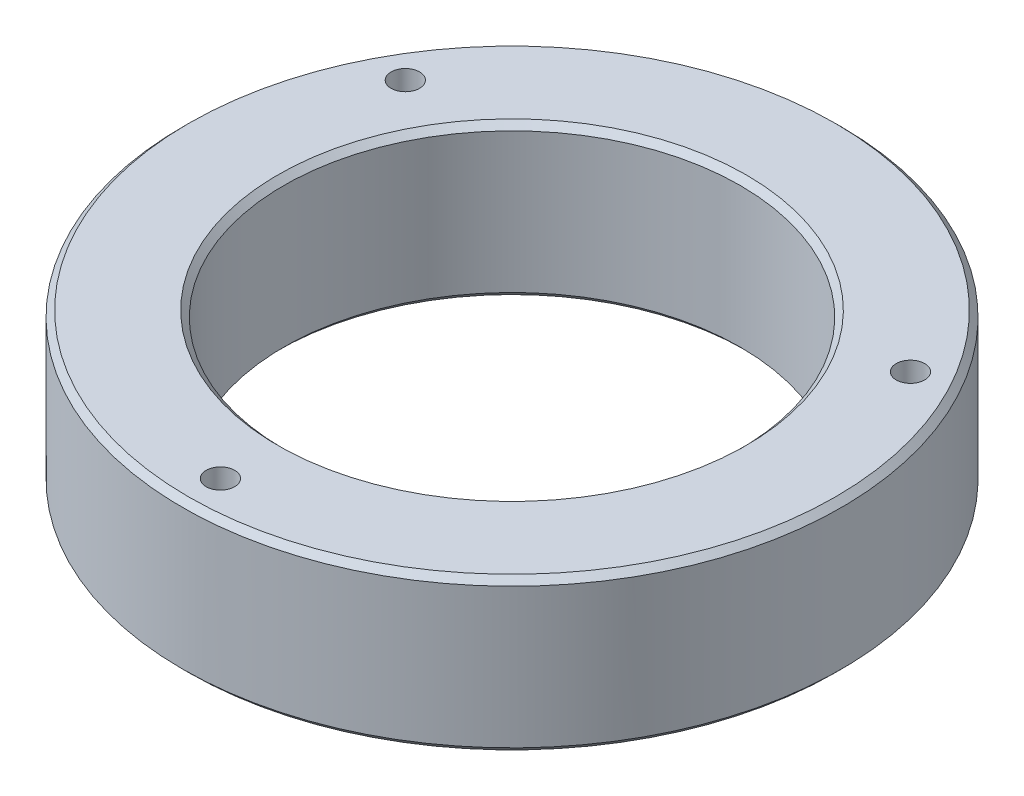
SolidWorks part; units mm, degrees
ref_plane "Front Plane" through (0, 0, 0) normal (1, 0, 0) x (0, 1, 0)
ref_plane "Top Plane" through (0, 0, 0) normal (0, 0, 1) x (0, 1, 0)
ref_plane "Right Plane" through (0, 0, 0) normal (0, 1, 0) x (-1, 0, 0)
sketch "Sketch1" plane through (0, 0, 0) normal (0, 0, 1) x (0, 1, 0)
  line L0 (-19.05, 82.5246) -> (19.05, 82.5246)
  line L1 (19.05, 82.5246) -> (19.05, 57.15)
  line L2 (19.05, 57.15) -> (-19.05, 57.15)
  line L3 (-19.05, 57.15) -> (-19.05, 82.5246)
  line L4 (-44.45, 0) -> (44.45, 0) construction
  point P6 (0, 0)
  dimension "D1" = 38.1
  dimension "D2" = 25.3746
  dimension "D3" = 82.5246
  dimension "D4" = 19.05
revolve "Revolve1" add sketch "Sketch1" angle 360 about L4
hole_wizard "CBORE for 1/4 Socket Head Cap Screw1" positions "Sketch3" profile "Sketch2" counterbore size "1/4" standard "ANSI Inch"
sketch "Sketch3" plane through (0, -19.05, 0) normal (0, -1, 0) x (-1, 0, 0)
  circle A0 centre (0, 0.0068) radius 73.0318 construction
  circle A1 centre (0, 0) radius 57.15 construction
  point P0 (0, -73.025)
  point P1 (-63.246, 36.5252)
  point P3 (63.246, 36.5252)
  dimension "D1" = 146.0637
  dimension "D2" = 63.246
  dimension "D3" = 63.246
  dimension "D4" = 0.0068
  dimension "D6" = 73.025
sketch "Sketch2" plane through (0, -19.05, 73.025) normal (1, 0, 0) x (0, 0, -1)
  line L0 (0, 0) -> (0, 40.2443)
  line L1 (0, 40.2443) -> (3.5687, 38.1)
  line L2 (3.5687, 38.1) -> (3.5687, 9.652)
  line L3 (3.5687, 9.652) -> (5.5626, 9.652)
  line L4 (5.5626, 9.652) -> (5.5626, 0)
  line L5 (5.5626, 0) -> (0, 0)
  line L10 (0, 40.2443) -> (-3.5687, 38.1) construction
  line L11 (0, -6.35) -> (0, 107.95) construction
  dimension "Hole Dia." = 7.1374
  dimension "Hole Depth" = 38.1
  dimension "C'Bore Dia." = 11.1252
  dimension "C'Bore Depth" = 9.652
  dimension "Drill Angle" = 118
hole_wizard "3/8-16 Tapped Hole2" positions "Sketch7" profile "Sketch6" tap size "3/8-16" standard "ANSI Inch"
sketch "Sketch7" plane through (0, -19.05, 0) normal (0, -1, 0) x (-1, 0, 0)
  circle A0 centre (0, -73.025) radius 5.5626 construction
  point P0 (-69.85, 0)
  point P1 (69.85, 0)
  dimension "D1" = 69.85
  dimension "D2" = 69.85
  dimension "D3" = 73.025
sketch "Sketch6" plane through (69.85, -19.05, 0) normal (1, 0, 0) x (0, 0, -1)
  line L0 (0, 0) -> (0, 27.7847)
  line L1 (0, 27.7847) -> (3.9687, 25.4)
  line L2 (3.9687, 25.4) -> (3.9687, 0)
  line L5 (3.9687, 0) -> (0, 0)
  line L10 (0, 27.7847) -> (-3.9687, 25.4) construction
  line L11 (0, -6.35) -> (0, 107.95) construction
  dimension "Tap Drill Dia." = 7.9375
  dimension "Tap Drill Depth" = 25.4
  dimension "Drill Angle" = 118
cosmetic thread "Hole Thread3"
cosmetic thread "Hole Thread4"
chamfer "Chamfer1" distance 1.524 angle 45 4 edges at (0, 19.05, -57.15) (0, -19.05, -57.15) (0, 19.05, -82.5246) (0, -19.05, -82.5246)
